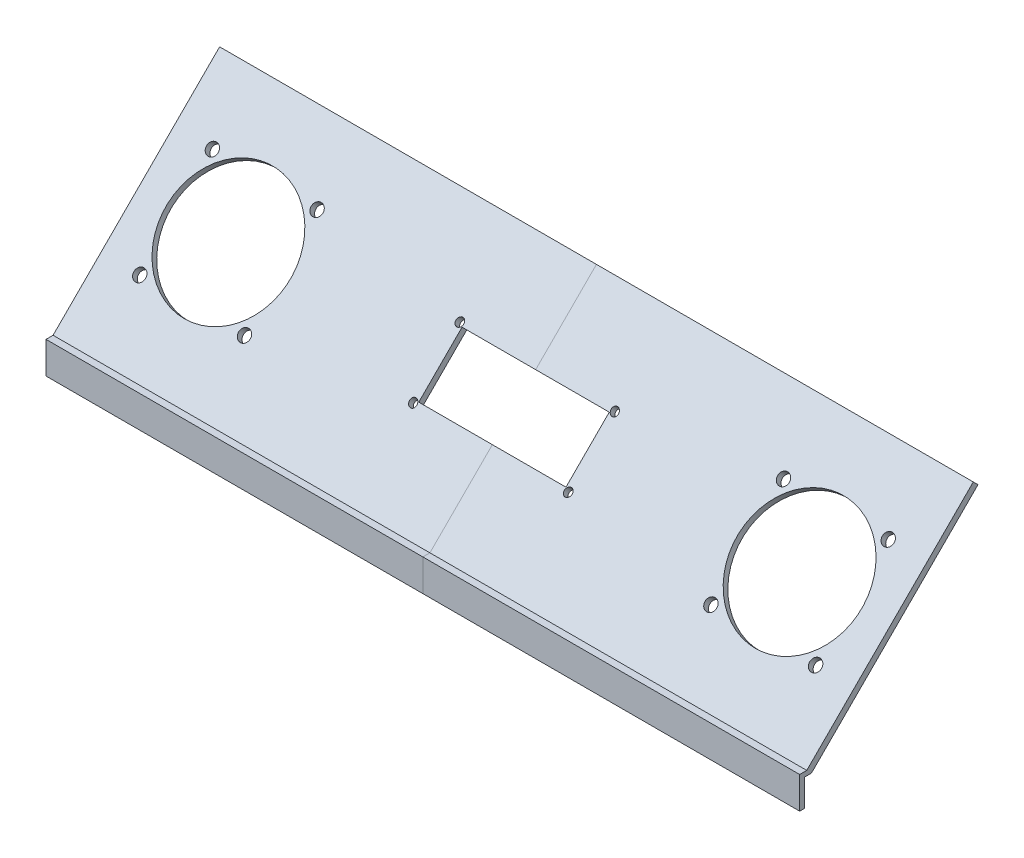
SolidWorks part; units mm, degrees
ref_plane "Front Plane" through (0, 0, 0) normal (0, 0, 1) x (1, 0, 0)
ref_plane "Top Plane" through (0, 0, 0) normal (0, 1, 0) x (1, 0, 0)
ref_plane "Right Plane" through (0, 0, 0) normal (1, 0, 0) x (0, 0, -1)
sketch "Sketch1" plane through (0, 0, 0) normal (1, 0, 0) x (0, 0, -1)
  line L0 (0, 0) -> (0, 11.5)
  line L1 (0, 11.5) -> (3, 11.5)
  line L2 (3, 11.5) -> (3, 13.5)
  line L3 (0, 0) -> (-2, 0)
  line L4 (3, 13.5) -> (-2, 13.5)
  line L5 (-2, 13.5) -> (-2, 0)
extrude "Boss-Extrude1" add sketch "Sketch1" along normal blind 160
sketch "Sketch2" plane through (0, 0, 0) normal (1, 0, 0) x (0, 0, -1)
  line L1 (3, 11.5) -> (24.2132, 32.7132)
  line L2 (1, 13.5) -> (71.7107, 84.2107)
  line L3 (3, 13.5) -> (1, 13.5)
  line L4 (3, 13.5) -> (-2, 13.5) construction
  line L5 (1, 13.5) -> (22.2132, 34.7132)
  line L7 (3, 13.5) -> (3, 11.5)
  line L9 (3, 11.5) -> (73.7107, 82.2107)
  line L10 (71.7107, 84.2107) -> (73.7107, 82.2107)
extrude "Boss-Extrude2" add sketch "Sketch2" along normal blind 160
sketch "Sketch3" plane through (0, 0, 2) normal (0, 0, 1) x (1, 0, 0)
  line L0 (0, 6.75) -> (10, 6.75)
  line L1 (0, 13.5) -> (0, 0) construction
  line L2 (160, 6.75) -> (152, 6.75)
  line L3 (160, 13.5) -> (160, 0) construction
sketch "Sketch4" plane through (0, 6.25, 6.25) normal (0, 0.7071, 0.7071) x (1, 0, 0)
  line L0 (160, 60.253) -> (128.75, 60.253)
  line L1 (160, 10.253) -> (160, 110.253) construction
  line L2 (128.75, 60.253) -> (128.75, 73.753)
  line L3 (160, 60.253) -> (160, 47.753)
  line L5 (128.75, 73.753) -> (160, 73.753)
  line L6 (128.75, 73.753) -> (128.75, 47.753)
  line L7 (128.75, 47.753) -> (160, 47.753)
  line L8 (160, 73.753) -> (160, 47.753)
  line M6 (160, 10.253) -> (160, 110.253)
extrude "Cut-Extrude1" cut sketch "Sketch4" against normal blind 10 contours L5 L2 L0 M6 | L6 L7 L0 M6
sketch "Sketch5" plane through (0, 6.25, 6.25) normal (0, 0.7071, 0.7071) x (1, 0, 0)
  line L0 (128.75, 73.753) -> (128.4439, 73.8869)
  line L1 (128.75, 60.753) -> (50.7631, 60.753)
  line L2 (128.75, 47.753) -> (128.75, 73.753) construction
  line L3 (126.9955, 74.5208) -> (127.1936, 74.9736)
  arc A0 (125.5283, 74.2089) -> (127.2747, 73.047) centre (126.9955, 74.5208) ccw
  arc A2 (128.6608, 75.2855) -> (126.9144, 76.4474) centre (127.1936, 74.9736) ccw
  ellipse E0 centre (127.0945, 74.7472) end of major axis (127.7517, 76.3659) minor radius 1.5959
  ellipse E1 centre (127.0945, 46.7589) end of major axis (127.7517, 45.1402) minor radius 1.5959
extrude "Cut-Extrude2" cut sketch "Sketch5" against normal blind 10
sketch "Sketch6" plane through (0, 6.25, 6.25) normal (0, 0.7071, 0.7071) x (1, 0, 0)
  line L0 (128.75, 60.753) -> (38.75, 60.753)
  line L1 (128.75, 47.753) -> (128.75, 73.753) construction
  line L3 (65.25, 34.253) -> (12.25, 34.253)
  line L4 (65.25, 34.253) -> (65.25, 87.253)
  line L5 (65.25, 87.253) -> (12.25, 87.253)
  line L6 (12.25, 34.253) -> (12.25, 87.253)
  line L7 (65.25, 34.253) -> (12.25, 87.253) construction
  line L8 (65.25, 87.253) -> (12.25, 34.253) construction
  circle A0 centre (38.75, 60.753) radius 26.5
extrude "Cut-Extrude3" cut sketch "Sketch6" against normal blind 10
sketch "Sketch7" plane through (0, 6.25, 6.25) normal (0, 0.7071, 0.7071) x (1, 0, 0)
  line L0 (38.75, 87.253) -> (38.75, 34.253)
  line L1 (12.24, 86.77) -> (15.8169, 83.2597)
  line L2 (12.24, 34.7361) -> (65.26, 34.7361)
  line L3 (12.24, 34.7361) -> (12.24, 86.77)
  line L4 (12.24, 86.77) -> (65.26, 86.77)
  line L5 (65.26, 34.7361) -> (65.26, 86.77)
  line L6 (12.24, 34.7361) -> (65.26, 86.77) construction
  line L7 (12.24, 86.77) -> (65.26, 34.7361) construction
  line L8 (12.24, 60.753) -> (65.26, 60.753)
  line L10 (15.8169, 83.2597) -> (16.5235, 82.552)
  circle A0 centre (38.75, 60.753) radius 26.5 construction
  circle A5 centre (16.5235, 82.552) radius 2.5
  circle A6 centre (60.9765, 82.552) radius 2.5
  circle A7 centre (60.9765, 38.9541) radius 2.5
  circle A8 centre (16.5235, 38.9541) radius 2.5
  point P5 (38.75, 60.753)
extrude "Cut-Extrude4" cut sketch "Sketch7" against normal blind 10
ref_plane "Plane1" through (160, 0, 0) normal (1, 0, 0) x (0, 0, -1)
mirror "Mirror4" about plane through (160, 0, 0) normal (1, 0, 0) of bodies 106
split "Split2" trim tools "Plane1" bodies to split 114 resulting bodies 115 116
